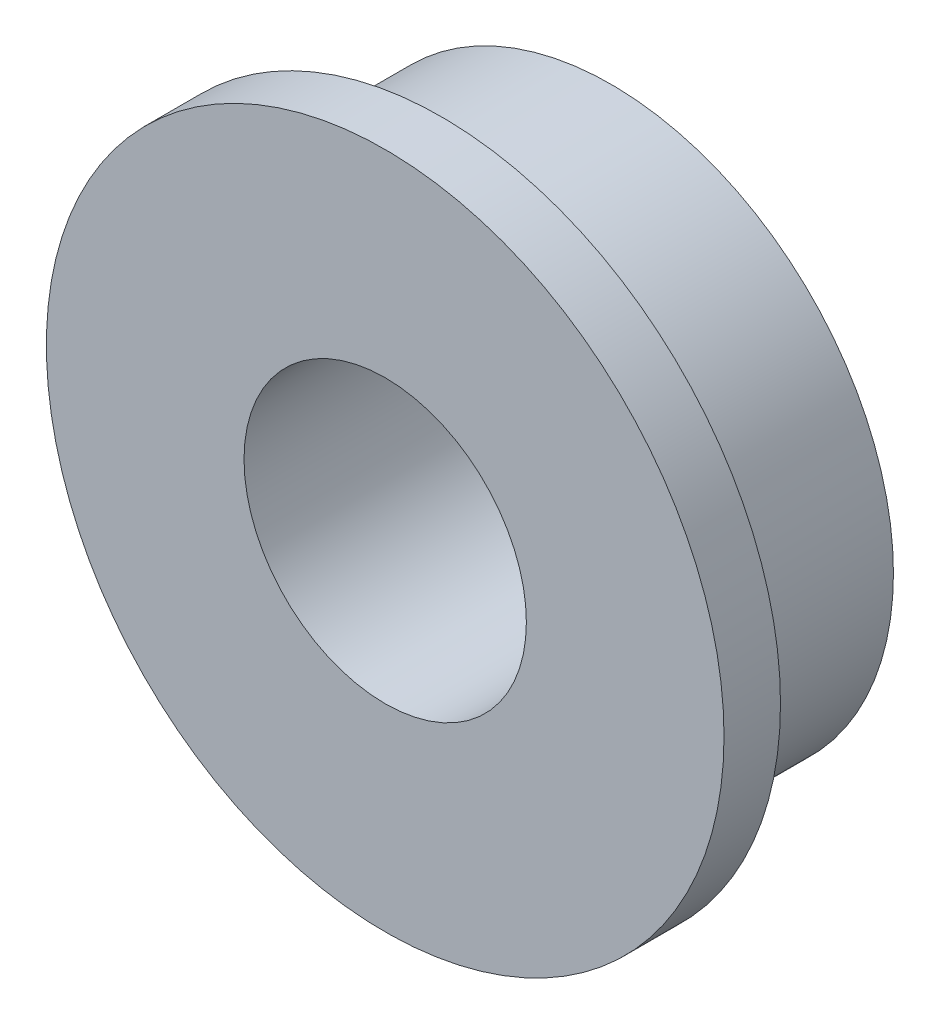
SolidWorks part; units mm, degrees
ref_plane "Front Plane" through (0, 0, 0) normal (0, 0, 1) x (1, 0, 0)
ref_plane "Top Plane" through (0, 0, 0) normal (0, 1, 0) x (1, 0, 0)
ref_plane "Right Plane" through (0, 0, 0) normal (1, 0, 0) x (0, 0, -1)
sketch "Sketch1" plane through (0, 0, 0) normal (0, 0, 1) x (1, 0, 0)
  circle A0 centre (0, 0) radius 2.5
  circle A1 centre (0, 0) radius 5
  dimension "D1" = 5
  dimension "D2" = 10
extrude "4" add sketch "Sketch1" along normal blind 4
sketch "Sketch2" plane through (0, 0, 4) normal (0, 0, 1) x (1, 0, 0)
  circle A0 centre (0, 0) radius 6
  circle A1 centre (0, 0) radius 2.5 construction
  circle A2 centre (0, 0) radius 2.5
extrude "Boss-Extrude2" add sketch "Sketch2" against normal blind 1
